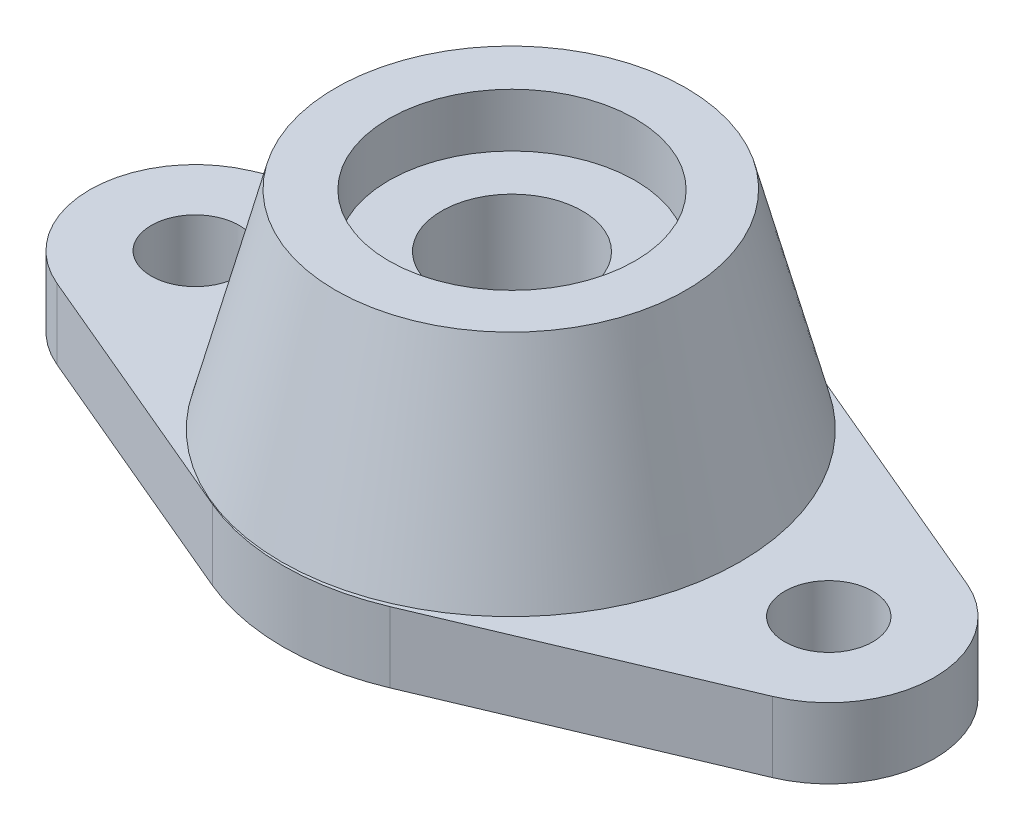
SolidWorks part; units mm, degrees
ref_plane "Front Plane" through (0, 0, 0) normal (0, 0, 1) x (1, 0, 0)
ref_plane "Top Plane" through (0, 0, 0) normal (0, 1, 0) x (1, 0, 0)
ref_plane "Right Plane" through (0, 0, 0) normal (1, 0, 0) x (0, 0, -1)
sketch "Sketch1" plane through (0, 0, 0) normal (0, 1, 0) x (1, 0, 0)
  line L0 (0, 0) -> (0, -140.4559) construction
  line L1 (-64.5583, 17.5505) -> (-16.0514, 38.026)
  line L2 (-64.5583, -17.5505) -> (-16.0514, -38.026)
  line L3 (64.5583, -17.5505) -> (16.0514, -38.026)
  line L4 (64.5583, 17.5505) -> (16.0514, 38.026)
  arc A0 (-16.0514, -38.026) -> (16.0514, -38.026) centre (0, 0) ccw
  arc A1 (-64.5583, 17.5505) -> (-64.5583, -17.5505) centre (-57.15, 0) ccw
  arc A2 (64.5583, -17.5505) -> (64.5583, 17.5505) centre (57.15, 0) ccw
  arc A3 (16.0514, 38.026) -> (-16.0514, 38.026) centre (0, 0) ccw
  circle A4 centre (-57.15, 0) radius 7.9375
  circle A5 centre (57.15, 0) radius 7.9375
  dimension "D1" = 38.1
  dimension "D2" = 82.55
  dimension "D4" = 19.05
  dimension "D5" = 41.275
  dimension "D6" = 15.875
  dimension "D3" = 114.3
extrude "Boss-Extrude1" add sketch "Sketch1" along normal blind 12.7
sketch "Sketch2" plane through (0, 0, 0) normal (0, 0, 1) x (1, 0, 0)
  line L0 (-0.2175, 13.2677) -> (-0.2175, 50.8)
  line L1 (-0.2175, 50.8) -> (31.4003, 50.8)
  line L3 (31.4003, 50.8) -> (41.1845, 13.2677)
  line L5 (41.1845, 13.2677) -> (-0.2175, 13.2677)
  line L6 (-16.0514, 0) -> (16.0514, 0) construction
  line L7 (0, 0) -> (-0.539, 78.1346) construction
  dimension "D1" = 50.8
  dimension "D2" = 82.55
  dimension "D3" = 63.5
revolve "Revolve1" add sketch "Sketch2" angle 360 about L0
sketch "Sketch3" plane through (0, 0, 0) normal (0, 0, 1) x (1, 0, 0)
  line L0 (0, 0) -> (0, 50.8) construction
  line L2 (0, 50.8) -> (22.225, 50.8)
  line L3 (31.4003, 50.8) -> (-31.8354, 50.8) construction
  line L4 (22.225, 50.8) -> (22.225, 41.148)
  line L5 (22.225, 41.148) -> (12.7, 41.148)
  line L6 (12.7, 41.148) -> (12.7, 25.4)
  line L7 (12.7, 25.4) -> (19.05, 19.05)
  line L8 (19.05, 19.05) -> (19.05, 13.2677)
  line L9 (-41.6195, 13.2677) -> (41.1845, 13.2677) construction
  line L10 (19.05, 13.2677) -> (19.05, 0)
  line L11 (64.5583, 0) -> (16.0514, 0) construction
  line L12 (19.05, 0) -> (0, 0)
  line L13 (0, 50.8) -> (0, 0)
  point P13 (22.225, 45.974)
  dimension "D1" = 9.652
  dimension "D2" = 44.45
  dimension "D3" = 25.4
  dimension "D4" = 19.05
  dimension "D5" = 25.4
  dimension "D6" = 38.1
revolve "Cut-Revolve1" cut sketch "Sketch3" angle 360 about L13
